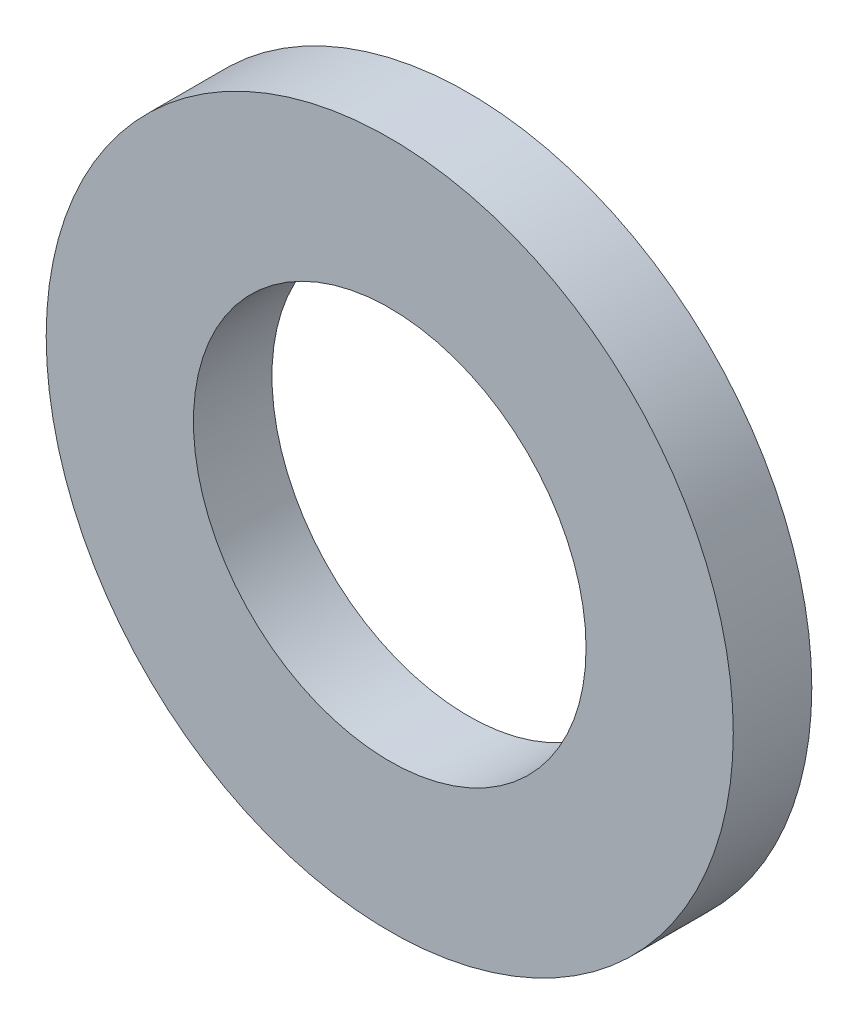
SolidWorks part; units mm, degrees
ref_plane "Front Plane" through (0, 0, 0) normal (0, 0, 1) x (1, 0, 0)
ref_plane "Top Plane" through (0, 0, 0) normal (0, 1, 0) x (1, 0, 0)
ref_plane "Right Plane" through (0, 0, 0) normal (1, 0, 0) x (0, 0, -1)
sketch "Sketch1" plane through (0, 0, 0) normal (0, 0, 1) x (1, 0, 0)
  circle A0 centre (0, 0) radius 17.5
  circle A1 centre (0, 0) radius 10
  dimension "D1" = 20
  dimension "D2" = 35
extrude "Boss-Extrude1" add sketch "Sketch1" along normal blind 4
